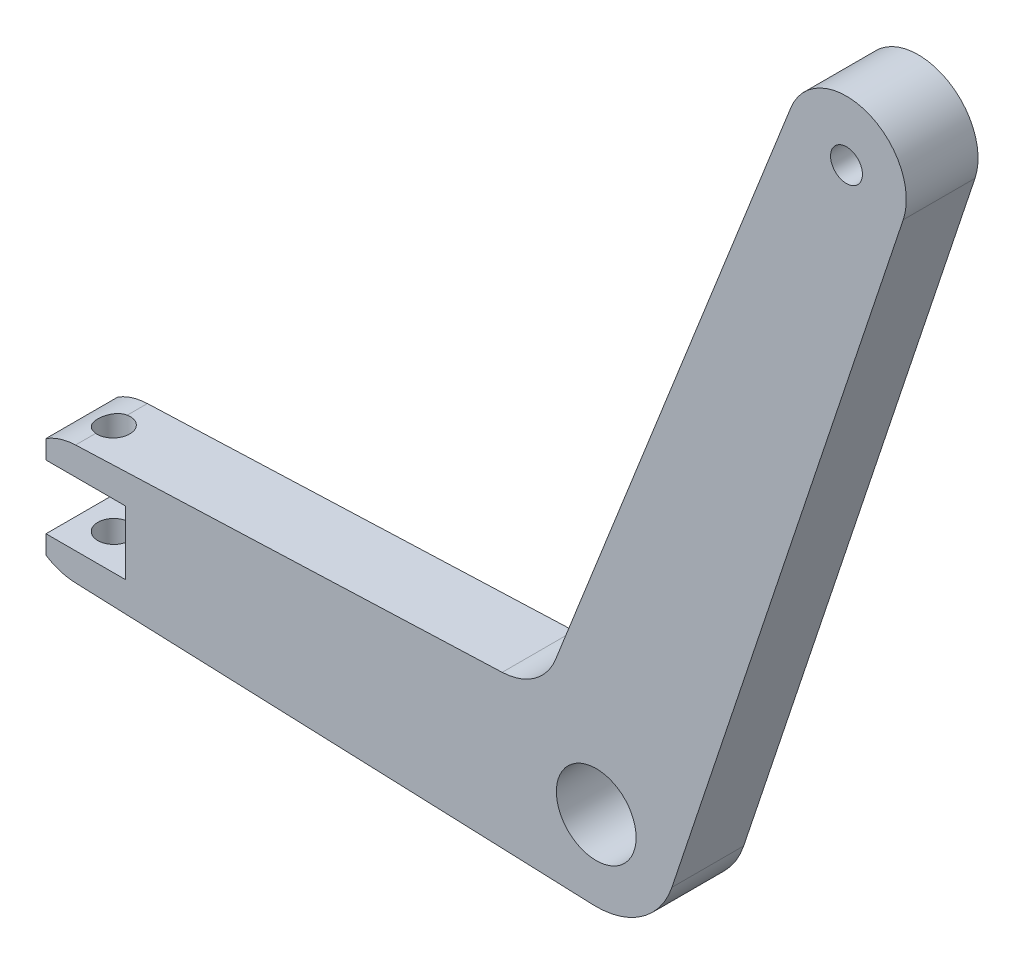
SolidWorks part; units mm, degrees
ref_plane "前视基准面" through (0, 0, 0) normal (0, 0, 1) x (1, 0, 0)
ref_plane "上视基准面" through (0, 0, 0) normal (0, 1, 0) x (1, 0, 0)
ref_plane "右视基准面" through (0, 0, 0) normal (1, 0, 0) x (0, 0, -1)
other "Configuration Table"
sketch "草图1" plane through (0, 0, 0) normal (0, 0, 1) x (1, 0, 0)
  line L0 (0, 0) -> (62.7607, 172.4336) construction
  line L1 (0, 0) -> (-130, 0) construction
  line L3 (76.9906, 167.6893) -> (18.9733, -6.3258)
  line L4 (-130.5769, 14.9889) -> (-23.5835, 19.1071)
  line L5 (48.8103, 177.9461) -> (-10.2101, 28.5835)
  line L6 (-130, -15) -> (-0.7709, -19.9851)
  arc A0 (-0.7709, -19.9851) -> (18.9733, -6.3258) centre (0, 0) ccw
  arc A1 (-130.5769, 14.9889) -> (-130, -15) centre (-130, 0) ccw
  arc A2 (76.9906, 167.6893) -> (48.8103, 177.9461) centre (62.7607, 172.4336) ccw
  arc A3 (-10.2101, 28.5835) -> (-23.5835, 19.1071) centre (-24.1604, 34.096) cw
  dimension "D1" = 15
extrude "凸台-拉伸1" add sketch "草图1" along normal blind 18
sketch "草图3" plane through (0, 0, 0) normal (0, 0, 1) x (1, 0, 0)
  circle A0 centre (0, 0) radius 10
  circle A1 centre (62.7607, 172.4336) radius 4
extrude "切除-拉伸1" cut sketch "草图3" along normal blind 18
ref_plane "基准面1" through (-130, 0, 0) normal (1, 0, 0) x (0, 0, -1)
sketch "草图4" plane through (0, 0, 0) normal (0, 1, 0) x (1, 0, 0)
  circle A0 centre (-130, -9) radius 4
extrude "切除-拉伸2" cut sketch "草图4" against normal mid plane 40
sketch "草图5" plane through (-130, 0, 0) normal (1, 0, 0) x (0, 0, -1)
  line L1 (-18, -8) -> (-18, 8)
  line L2 (-18, 8) -> (0, 8)
  line L3 (0, 8) -> (0, -8)
  line L4 (-18, -8) -> (0, -8)
extrude "切除-拉伸3" cut sketch "草图5" against normal blind 28 from offset 12
sketch "草图8" plane through (0, 0, 0) normal (0, 0, 1) x (1, 0, 0)
  line L1 (-145, 0) -> (-145, 20)
  line L2 (-145, 20) -> (-138, 20)
  line L3 (-138, 20) -> (-138, -20)
  line L4 (-138, -20) -> (-145, -20)
  line L5 (-145, -20) -> (-145, 0)
extrude "切除-拉伸5" cut sketch "草图8" along normal blind 18
